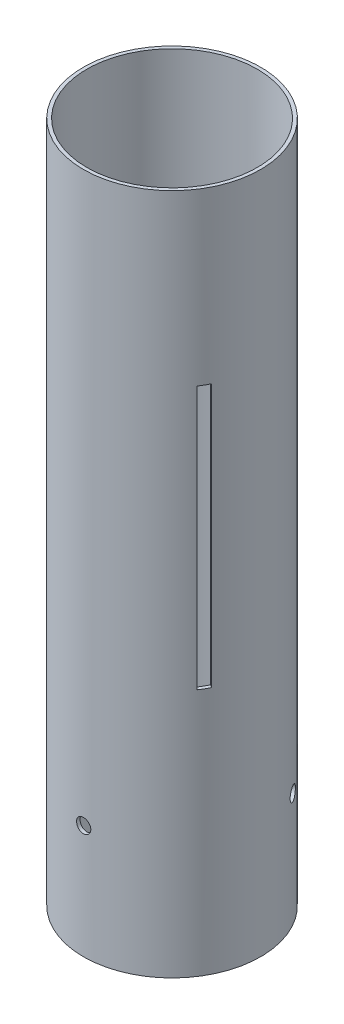
SolidWorks part; units mm, degrees
material "S-Glass Fiber"
ref_plane "Front Plane" through (0, 0, 0) normal (0, 0, 1) x (1, 0, 0)
ref_plane "Top Plane" through (0, 0, 0) normal (0, 1, 0) x (1, 0, 0)
ref_plane "Right Plane" through (0, 0, 0) normal (1, 0, 0) x (0, 0, -1)
sketch "Sketch2" plane through (0, 0, 0) normal (0, 1, 0) x (1, 0, 0)
  circle A0 centre (0, 0) radius 39.624
  circle A1 centre (0, 0) radius 38.1
  dimension "D1" = 79.248
  dimension "D2" = 76.2
extrude "Boss-Extrude1" add sketch "Sketch2" along normal blind 304.8 contours A1 | A0
sketch "Sketch3" plane through (0, 0, 0) normal (0, 0, 1) x (1, 0, 0)
  line L0 (-2.3812, 0) -> (2.3812, 0)
  line L1 (-39.624, 0) -> (39.624, 0) construction
  line L2 (2.3812, 110.998) -> (2.3812, 228.6)
  line L3 (2.3812, 228.6) -> (-2.3813, 228.6)
  line L4 (-2.3813, 228.6) -> (-2.3813, 110.998)
  line L5 (-2.3813, 228.6) -> (-2.3813, 110.998)
  line L6 (39.624, 304.8) -> (-39.624, 304.8) construction
  line L7 (2.3812, 228.6) -> (-2.3813, 228.6)
  line L8 (2.3812, 228.6) -> (2.3812, 110.998)
  line L9 (2.3812, 110.998) -> (-2.3813, 110.998)
  line L10 (-2.3813, 228.6) -> (-2.3813, 110.998)
  point P0 (0, 228.6)
  point P6 (0, 0)
  dimension "D1" = 4.7625
  dimension "D2" = 228.6
  dimension "D3" = 117.602
  dimension "D4" = 76.2
  dimension "D5" = 4.7625
extrude "Cut-Extrude1" cut sketch "Sketch3" against normal through all contours L9 L2 L3 L4
pattern_circular "CirPattern1" count 3 over 360 about axis through (0, 0, 0) along (0, 1, 0) of "Cut-Extrude1"
sketch "Sketch4" plane through (0, 0, 0) normal (0, 0, 1) x (1, 0, 0)
  line L0 (-39.624, 0) -> (39.624, 0) construction
  circle A0 centre (0, 50.8) radius 3.175
  dimension "D1" = 6.35
  dimension "D2" = 50.8
extrude "Cut-Extrude3" cut sketch "Sketch4" along normal through all
pattern_circular "CirPattern2" count 3 over 360 about axis through (0, 304.8, 0) along (0, -1, 0) of "Cut-Extrude3"
